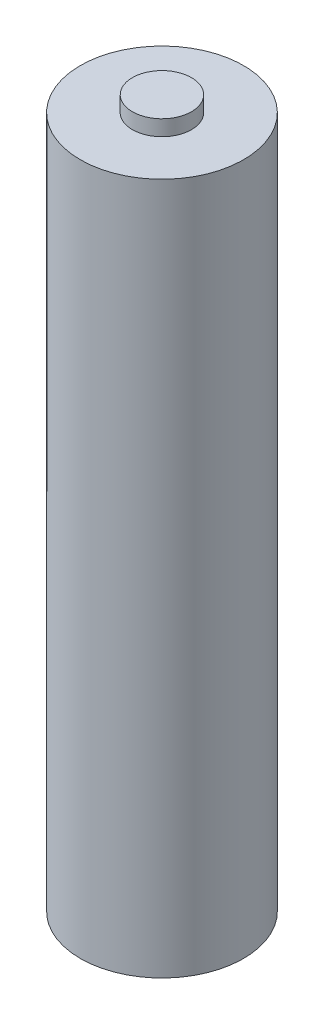
SolidWorks part; units mm, degrees
ref_plane "Front Plane" through (0, 0, 0) normal (0, 0, 1) x (1, 0, 0)
ref_plane "Top Plane" through (0, 0, 0) normal (0, 1, 0) x (1, 0, 0)
ref_plane "Right Plane" through (0, 0, 0) normal (1, 0, 0) x (0, 0, -1)
sketch "Sketch1" plane through (0, 0, 0) normal (0, 1, 0) x (1, 0, 0)
  circle A0 centre (0, 0) radius 5.25
extrude "Boss-Extrude1" add sketch "Sketch1" along normal blind 44.5
sketch "Sketch2" plane through (0, 44.5, 0) normal (0, 1, 0) x (1, 0, 0)
  circle A0 centre (0, 0) radius 1.9
extrude "Boss-Extrude2" add sketch "Sketch2" along normal blind 1
